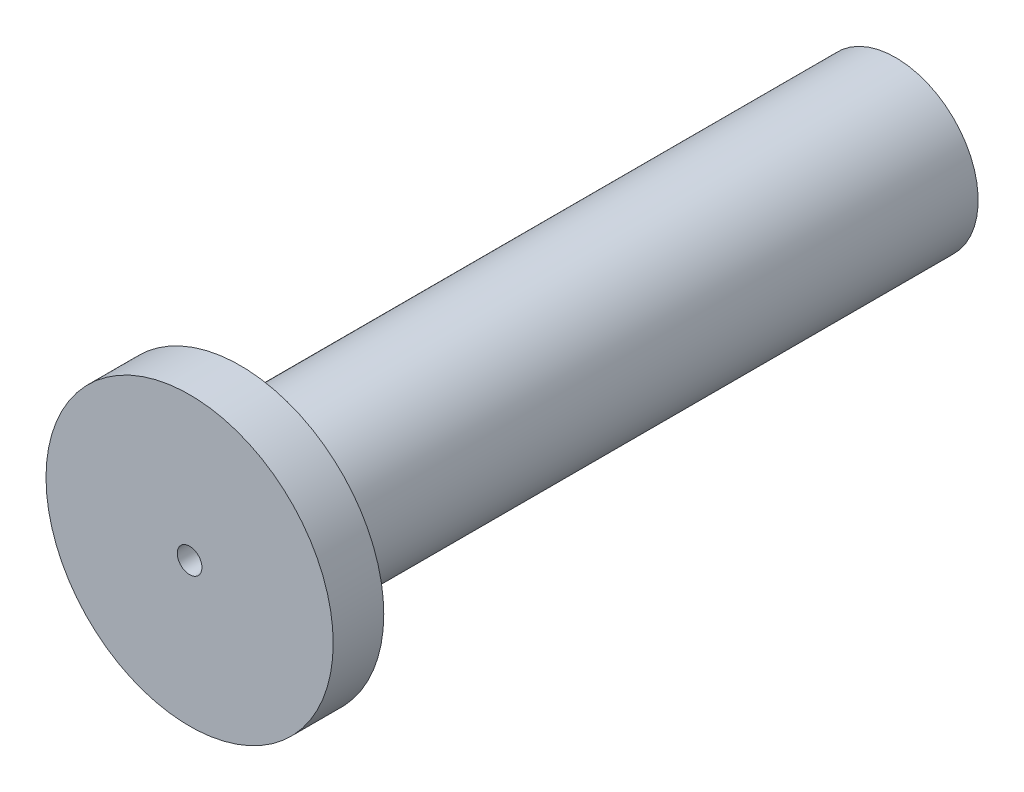
SolidWorks part; units mm, degrees
ref_plane "Front Plane" through (0, 0, 0) normal (0, 0, 1) x (1, 0, 0)
ref_plane "Top Plane" through (0, 0, 0) normal (0, 1, 0) x (1, 0, 0)
ref_plane "Right Plane" through (0, 0, 0) normal (1, 0, 0) x (0, 0, -1)
sketch "Sketch1" plane through (0, 0, 0) normal (0, 1, 0) x (1, 0, 0)
  line L0 (0, 0) -> (23, 0)
  line L1 (23, 0) -> (23, 8.1)
  line L2 (23, 8.1) -> (13.2, 8.1)
  line L3 (13.2, 8.1) -> (13.2, 113.1)
  line L4 (13.2, 113.1) -> (10.2, 113.1)
  line L5 (10.2, 113.1) -> (10.2, 8.1)
  line L6 (10.2, 8.1) -> (0, 8.1)
  line L7 (0, 8.1) -> (0, 0)
  dimension "D1" = 23
  dimension "D2" = 8.1
  dimension "D3" = 9.8
  dimension "D4" = 105
  dimension "D5" = 3
  dimension "D6" = 105
revolve "Revolve1" add sketch "Sketch1" angle 360 about L7
sketch "Sketch2" plane through (0, 0, 0) normal (0, 0, 1) x (1, 0, 0)
  circle A0 centre (0, 0) radius 1.975
  dimension "D1" = 3.95
extrude "Cut-Extrude1" cut sketch "Sketch2" against normal up to next
